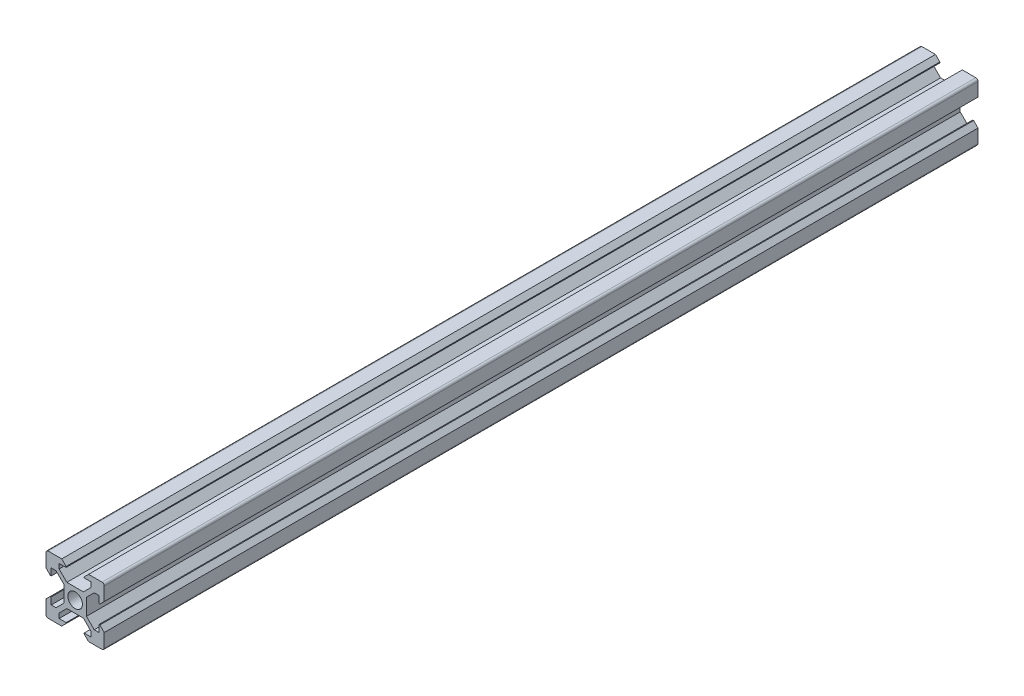
SolidWorks part; units mm, degrees
ref_plane "Alzado" through (0, 0, 0) normal (0, 0, 1) x (1, 0, 0)
ref_plane "Planta" through (0, 0, 0) normal (0, 1, 0) x (1, 0, 0)
ref_plane "Vista lateral" through (0, 0, 0) normal (1, 0, 0) x (0, 0, -1)
sketch "Croquis1" plane through (0, 0, 0) normal (0, 0, 1) x (1, 0, 0)
  line L0 (-4.6, 10) -> (-3.1, 8.5)
  line L3 (-4.6, 10) -> (-9.25, 10)
  line L5 (-3.1, 8.5) -> (-3.1, 8.2)
  line L6 (-3.1, 8.2) -> (-5.5, 8.2)
  line L7 (-5.5, 8.2) -> (-5.5, 6.5607)
  line L8 (-5.5, 6.5607) -> (-2.84, 3.9007)
  line L9 (-2.84, 3.9007) -> (0, 3.9007)
  line L10 (0, 0) -> (-15.3499, 15.3499) construction
  line L11 (-3.9007, 2.84) -> (-3.9007, 0)
  line L12 (-6.5607, 5.5) -> (-3.9007, 2.84)
  line L13 (-8.2, 5.5) -> (-6.5607, 5.5)
  line L14 (-8.2, 3.1) -> (-8.2, 5.5)
  line L15 (-8.5, 3.1) -> (-8.2, 3.1)
  line L16 (-10, 4.6) -> (-10, 9.25)
  line L17 (-10, 4.6) -> (-8.5, 3.1)
  line L18 (10, 4.6) -> (8.5, 3.1)
  line L19 (10, 4.6) -> (10, 9.25)
  line L20 (8.5, 3.1) -> (8.2, 3.1)
  line L21 (8.2, 3.1) -> (8.2, 5.5)
  line L22 (8.2, 5.5) -> (6.5607, 5.5)
  line L23 (6.5607, 5.5) -> (3.9007, 2.84)
  line L24 (3.9007, 2.84) -> (3.9007, 0)
  line L25 (5.5, 6.5607) -> (2.84, 3.9007)
  line L26 (5.5, 8.2) -> (5.5, 6.5607)
  line L27 (3.1, 8.2) -> (5.5, 8.2)
  line L28 (3.1, 8.5) -> (3.1, 8.2)
  line L29 (4.6, 10) -> (9.25, 10)
  line L30 (4.6, 10) -> (3.1, 8.5)
  line L31 (2.84, 3.9007) -> (0, 3.9007)
  line L32 (4.6, -10) -> (3.1, -8.5)
  line L33 (4.6, -10) -> (9.25, -10)
  line L34 (3.1, -8.5) -> (3.1, -8.2)
  line L35 (3.1, -8.2) -> (5.5, -8.2)
  line L36 (5.5, -8.2) -> (5.5, -6.5607)
  line L37 (5.5, -6.5607) -> (2.84, -3.9007)
  line L38 (2.84, -3.9007) -> (0, -3.9007)
  line L39 (6.5607, -5.5) -> (3.9007, -2.84)
  line L40 (8.2, -5.5) -> (6.5607, -5.5)
  line L41 (8.2, -3.1) -> (8.2, -5.5)
  line L42 (8.5, -3.1) -> (8.2, -3.1)
  line L43 (10, -4.6) -> (10, -9.25)
  line L44 (10, -4.6) -> (8.5, -3.1)
  line L45 (3.9007, -2.84) -> (3.9007, 0)
  line L46 (-10, -4.6) -> (-8.5, -3.1)
  line L47 (-10, -4.6) -> (-10, -9.25)
  line L48 (-8.5, -3.1) -> (-8.2, -3.1)
  line L49 (-8.2, -3.1) -> (-8.2, -5.5)
  line L50 (-8.2, -5.5) -> (-6.5607, -5.5)
  line L51 (-6.5607, -5.5) -> (-3.9007, -2.84)
  line L52 (-3.9007, -2.84) -> (-3.9007, 0)
  line L53 (-5.5, -6.5607) -> (-2.84, -3.9007)
  line L54 (-5.5, -8.2) -> (-5.5, -6.5607)
  line L55 (-3.1, -8.2) -> (-5.5, -8.2)
  line L56 (-3.1, -8.5) -> (-3.1, -8.2)
  line L57 (-4.6, -10) -> (-9.25, -10)
  line L58 (-4.6, -10) -> (-3.1, -8.5)
  line L59 (-2.84, -3.9007) -> (0, -3.9007)
  circle A0 centre (0, 0) radius 2.5
  arc A1 (-9.25, 10) -> (-10, 9.25) centre (-9.25, 9.25) ccw
  arc A2 (10, 9.25) -> (9.25, 10) centre (9.25, 9.25) ccw
  arc A3 (9.25, -10) -> (10, -9.25) centre (9.25, -9.25) ccw
  arc A4 (-10, -9.25) -> (-9.25, -10) centre (-9.25, -9.25) ccw
  point P18 (-10, 10)
  point P37 (10, 10)
  point P55 (10, -10)
  point P73 (-10, -10)
  point P79 (0, 0)
  dimension "D1" = 5
  dimension "D5" = 0.75
  dimension "D2" = 10
  dimension "D3" = 10
  dimension "D4" = 4.6
  dimension "D6" = 5.5
  dimension "D7" = 135
  dimension "D8" = 0.75
  dimension "D9" = 225
  dimension "D10" = 2.84
  dimension "D11" = 1.8
  dimension "D12" = 3.1
  dimension "D13" = 4
extrude "Saliente-Extruir1" add sketch "Croquis1" along normal blind 300
